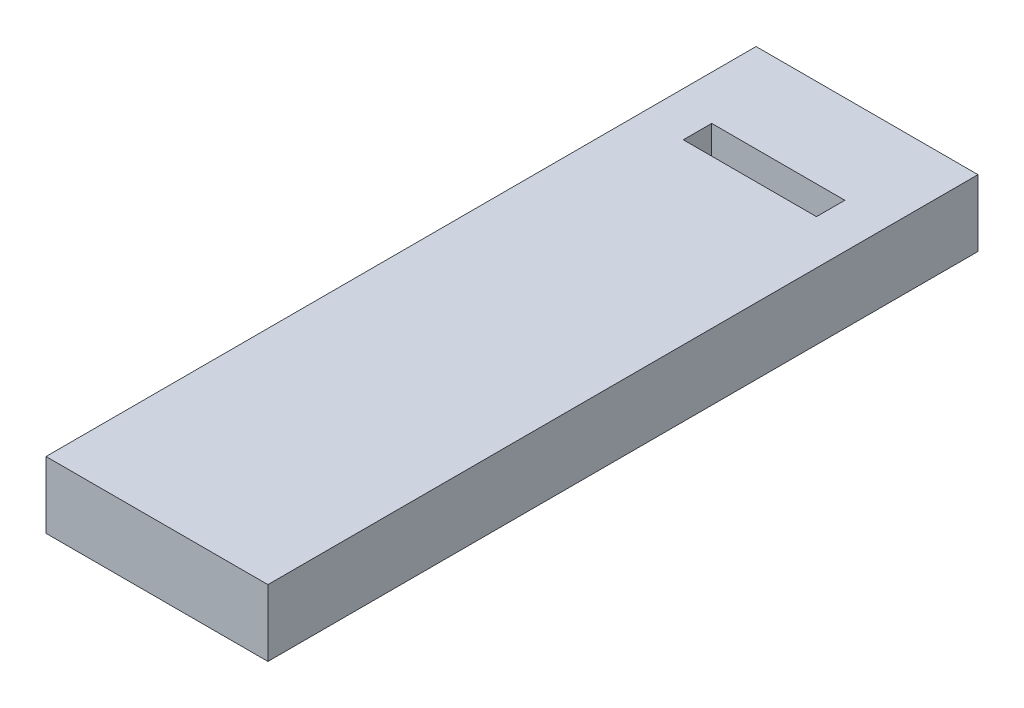
SolidWorks part; units mm, degrees
ref_plane "Front Plane" through (0, 0, 0) normal (0, 0, 1) x (1, 0, 0)
ref_plane "Top Plane" through (0, 0, 0) normal (0, 1, 0) x (1, 0, 0)
ref_plane "Right Plane" through (0, 0, 0) normal (1, 0, 0) x (0, 0, -1)
sketch "Sketch1" plane through (0, 0, 0) normal (0, 1, 0) x (1, 0, 0)
  line L1 (-31.75, -101.6) -> (31.75, -101.6)
  line L2 (-31.75, -101.6) -> (-31.75, 101.6)
  line L3 (-31.75, 101.6) -> (31.75, 101.6)
  line L4 (31.75, -101.6) -> (31.75, 101.6)
  line L5 (-31.75, -101.6) -> (31.75, 101.6) construction
  line L6 (-31.75, 101.6) -> (31.75, -101.6) construction
  point P0 (0, 0)
  dimension "D1" = 63.5
  dimension "D2" = 203.2
extrude "Boss-Extrude1" add sketch "Sketch1" along normal blind 19.05
sketch "Sketch2" plane through (0, 0, -101.6) normal (0, 0, -1) x (-1, 0, 0)
  line L1 (-31.75, 0) -> (31.75, 0) construction
  circle A0 centre (0, 0) radius 4.7625
  dimension "D1" = 9.525
extrude "Cut-Extrude1" cut sketch "Sketch2" against normal blind 25.4
ref_plane "Plane1" through (0, 0, 0) normal (0, -1, 0) x (-1, 0, 0)
sketch "Sketch3" plane through (0, 0, 0) normal (0, -1, 0) x (-1, 0, 0)
  line L0 (4.7625, 76.2) -> (-4.7625, 76.2) construction
  line L1 (-20.6375, -96.8375) -> (20.6375, -96.8375)
  line L2 (-26.9875, -90.4875) -> (-26.9875, 37.592)
  line L3 (-23.8125, 76.2) -> (23.8125, 76.2)
  line L4 (26.9875, -90.4875) -> (26.9875, 37.592)
  line L5 (23.8125, 68.072) -> (-23.8125, 68.072)
  line L6 (20.6375, 43.942) -> (-20.6375, 43.942)
  line L7 (26.9875, 71.247) -> (26.9875, 73.025)
  line L8 (-26.9875, 71.247) -> (-26.9875, 73.025)
  line L14 (4.7625, 101.6) -> (4.7625, 76.2)
  line L15 (4.7625, 76.2) -> (-4.7625, 76.2)
  line L16 (-4.7625, 76.2) -> (-4.7625, 101.6)
  line L17 (-4.7625, 101.6) -> (-31.75, 101.6)
  line L18 (-31.75, 101.6) -> (-31.75, -101.6)
  line L19 (-31.75, -101.6) -> (31.75, -101.6)
  line L20 (31.75, -101.6) -> (31.75, 101.6)
  line L21 (31.75, 101.6) -> (4.7625, 101.6)
  line L25 (-4.7625, 101.6) -> (-31.75, 101.6) construction
  line L26 (-31.75, 101.6) -> (-31.75, -101.6) construction
  line L27 (-31.75, -101.6) -> (31.75, -101.6) construction
  line L28 (31.75, -101.6) -> (31.75, 101.6) construction
  line L29 (31.75, 101.6) -> (4.7625, 101.6) construction
  arc A0 (-26.9875, -90.4875) -> (-20.6375, -96.8375) centre (-20.6375, -90.4875) ccw
  arc A1 (20.6375, -96.8375) -> (26.9875, -90.4875) centre (20.6375, -90.4875) ccw
  arc A2 (26.9875, 73.025) -> (23.8125, 76.2) centre (23.8125, 73.025) ccw
  arc A3 (-23.8125, 76.2) -> (-26.9875, 73.025) centre (-23.8125, 73.025) ccw
  arc A4 (20.6375, 43.942) -> (26.9875, 37.592) centre (20.6375, 37.592) cw
  arc A5 (-20.6375, 43.942) -> (-26.9875, 37.592) centre (-20.6375, 37.592) ccw
  arc A6 (-23.8125, 68.072) -> (-26.9875, 71.247) centre (-23.8125, 71.247) cw
  arc A7 (23.8125, 68.072) -> (26.9875, 71.247) centre (23.8125, 71.247) ccw
  point P0 (0, 0)
  point P33 (-26.9875, 68.072)
  point P36 (26.9875, 68.072)
  dimension "D5" = 6.35
  dimension "D6" = 8.128
  dimension "D8" = 6.35
  dimension "D9" = 3.175
  dimension "D2" = 9.525
  dimension "D3" = 9.525
  dimension "D4" = 9.525
  dimension "D7" = 24.13
  dimension "D1" = 0
extrude "Cut-Extrude2" cut sketch "Sketch3" against normal blind 9.525
sketch "Sketch5" plane through (0, 0, 0) normal (0, 1, 0) x (1, 0, 0)
  line L0 (4.7625, 76.2) -> (23.8125, 76.2) construction
  line L1 (19.05, 76.2) -> (-19.05, 76.2)
  line L2 (19.05, 76.2) -> (19.05, 68.072)
  line L3 (19.05, 68.072) -> (-19.05, 68.072)
  line L4 (-19.05, 76.2) -> (-19.05, 68.072)
  line L5 (0, 0) -> (0, 132.0825) construction
  dimension "D1" = 8.128
  dimension "D2" = 38.1
extrude "Cut-Extrude4" cut sketch "Sketch5" along normal through all
sketch "Sketch6" plane through (0, 0, 0) normal (0, 1, 0) x (1, 0, 0)
  line L1 (-26.9875, 71.247) -> (26.9875, 71.247)
  line L2 (-26.9875, 71.247) -> (-26.9875, 37.592)
  line L3 (-26.9875, 37.592) -> (26.9875, 37.592)
  line L4 (26.9875, 71.247) -> (26.9875, 37.592)
extrude "Cut-Extrude5" cut sketch "Sketch6" along normal blind 2.159
